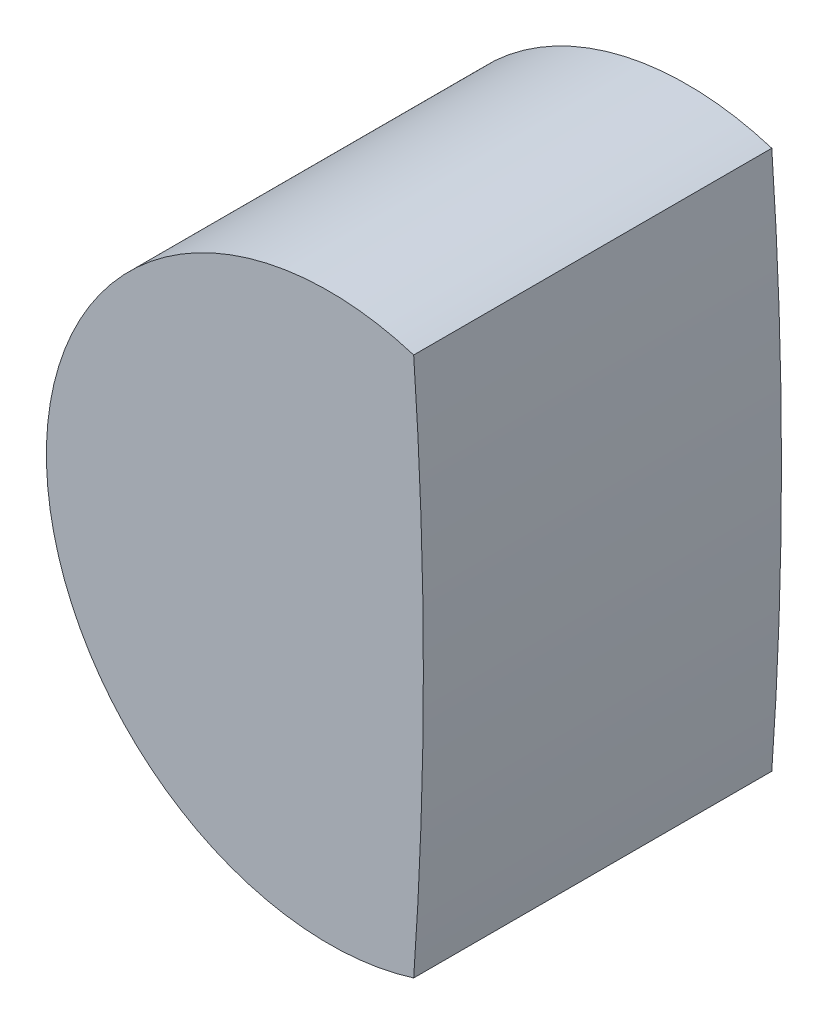
SolidWorks part; units mm, degrees
material "Acrylique (impact moyen-haut)"
ref_plane "Plan de face" through (0, 0, 0) normal (0, 0, 1) x (1, 0, 0)
ref_plane "Plan de dessus" through (0, 0, 0) normal (0, 1, 0) x (1, 0, 0)
ref_plane "Plan de droite" through (0, 0, 0) normal (1, 0, 0) x (0, 0, -1)
sketch "Esquisse1" plane through (0, 0, 0) normal (0, 0, 1) x (1, 0, 0)
  line L0 (0, 0) -> (-19.5, 0) construction
  arc A0 (0.4487, 1.4313) -> (0.4487, -1.4313) centre (0, 0) ccw
  arc A1 (0.4487, -1.4313) -> (0.4487, 1.4313) centre (-19.5, 0) ccw
  dimension "D1" = 3
  dimension "D3" = 40
  dimension "D2" = 19.5
extrude "Boss.-Extru.1" add sketch "Esquisse1" along normal blind 1.9
